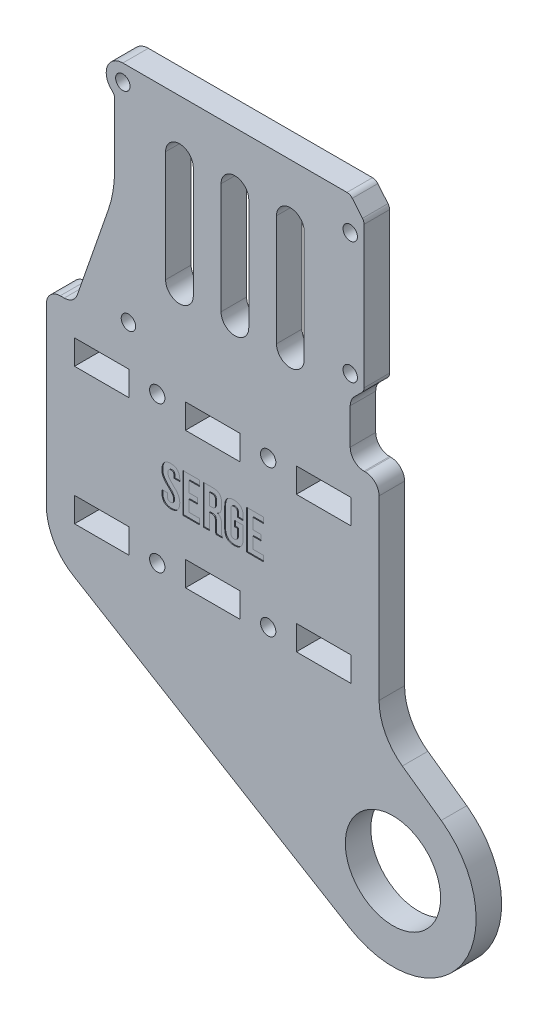
SolidWorks part; units mm, degrees
ref_plane "Front Plane" through (0, 0, 0) normal (0, 0, 1) x (1, 0, 0)
ref_plane "Top Plane" through (0, 0, 0) normal (0, 1, 0) x (1, 0, 0)
ref_plane "Right Plane" through (0, 0, 0) normal (1, 0, 0) x (0, 0, -1)
sketch "Sketch1" plane through (0, 0, 0) normal (0, 0, 1) x (1, 0, 0)
  line L0 (-38.1, 0) -> (38.1, 0) construction
  line L1 (31.65, -12.8) -> (19.15, -12.8)
  line L2 (38.1, -12.8) -> (38.1, 12.8)
  line L3 (31.65, 12.8) -> (19.15, 12.8)
  line L4 (-38.1, -12.8) -> (-38.1, 12.8)
  line L5 (38.1, -12.8) -> (-38.1, 12.8) construction
  line L6 (38.1, 12.8) -> (-38.1, -12.8) construction
  line L7 (6.25, 18.442) -> (-6.25, 18.442)
  line L8 (-19.15, -18.442) -> (-31.65, -12.8) construction
  line L9 (-19.15, -12.8) -> (-31.65, -18.442) construction
  line L10 (6.25, -12.8) -> (-6.25, -12.8)
  line L11 (-19.15, -12.8) -> (-31.65, -12.8)
  line L12 (31.65, -12.8) -> (31.65, -18.442)
  line L13 (19.15, -12.8) -> (19.15, -18.442)
  line L14 (12.6, 101.346) -> (12.6, 25.146) construction
  line L15 (-19.15, 12.8) -> (-19.15, 18.442)
  line L16 (-19.15, 18.442) -> (-31.65, 18.442)
  line L17 (-31.65, 12.8) -> (-31.65, 18.442)
  line L18 (-19.15, 12.8) -> (-31.65, 18.442) construction
  line L19 (-19.15, 18.442) -> (-31.65, 12.8) construction
  line L20 (-6.25, 12.8) -> (-6.25, 18.442)
  line L21 (6.25, 12.8) -> (6.25, 18.442)
  line L22 (31.65, 18.442) -> (19.15, 18.442)
  line L23 (19.15, 12.8) -> (19.15, 18.442)
  line L24 (31.65, 12.8) -> (31.65, 18.442)
  line L25 (-19.15, 12.8) -> (-31.65, 12.8)
  line L26 (6.25, 12.8) -> (-6.25, 12.8)
  line L27 (-38.1, 12.8) -> (-38.1, 25.146)
  line L28 (-38.1, 25.146) -> (-31.65, 25.146)
  line L29 (31.65, 25.146) -> (38.1, 25.146)
  line L30 (38.1, 25.146) -> (38.1, 12.8)
  line L31 (31.65, -18.442) -> (19.15, -18.442)
  line L32 (6.25, -12.8) -> (6.25, -18.442)
  line L33 (-6.25, -12.8) -> (-6.25, -18.442)
  line L34 (-31.65, -12.8) -> (-31.65, -18.442)
  line L35 (-19.15, -18.442) -> (-31.65, -18.442)
  line L36 (-19.15, -12.8) -> (-19.15, -18.442)
  line L37 (6.25, -18.442) -> (-6.25, -18.442)
  line L38 (31.65, -12.8) -> (19.15, -12.8)
  line L39 (-19.15, -12.8) -> (-31.65, -12.8)
  line L40 (6.25, -12.8) -> (-6.25, -12.8)
  line L41 (6.25, 12.8) -> (19.15, 12.8) construction
  line L42 (-38.1, -25.146) -> (31.4317, -67.1098)
  line L43 (38.1, -25.146) -> (52.3299, -35.2858)
  line L48 (-6.25, 12.8) -> (-19.15, 12.8) construction
  line L49 (31.65, 25.146) -> (31.65, 101.346)
  line L50 (31.65, 101.346) -> (-6.45, 101.346)
  line L51 (-6.45, 101.346) -> (-31.65, 25.146)
  line L52 (-6.45, 81.122) -> (-6.45, 25.146)
  line L53 (-6.45, 25.146) -> (-24.9618, 25.146)
  line L54 (-6.45, 81.122) -> (-24.9618, 25.146)
  line L55 (-38.1, -12.8) -> (-38.1, -25.146)
  line L56 (-0.4211, 99.3522) -> (-25.6211, 23.1522) construction
  line L58 (38.1, -12.8) -> (38.1, -25.146)
  arc A0 (31.4317, -67.1098) -> (52.3299, -35.2858) centre (41.275, -50.8) ccw
  circle A1 centre (12.7, 16.7687) radius 1.7526
  circle A2 centre (-12.7, 16.7687) radius 1.7526
  circle A3 centre (12.7, -16.7687) radius 1.7526
  circle A4 centre (-12.7, -16.7687) radius 1.7526
  circle A5 centre (12.6, 94.996) radius 2.413
  circle A6 centre (41.275, -50.8) radius 10.9125
  point P0 (0, 0)
  point P8 (-25.4, 15.621)
  point P37 (-25.4, -15.621)
  point P70 (-3.225, -28.575)
  dimension "D3" = 12.5
  dimension "D5" = 50.8
  dimension "D6" = 41.275
  dimension "D8" = 3.5052
  dimension "D13" = 3.5052
  dimension "D11" = 4.826
  dimension "D19" = 21.825
  dimension "D7" = 38.1
  dimension "D1" = 25.6
  dimension "D2" = 76.2
  dimension "D4" = 5.642
  dimension "D9" = 12.7
  dimension "D10" = 3
  dimension "D12" = 3.9688
  dimension "D14" = 3.9688
  dimension "D15" = 76.2
  dimension "D16" = 38.1
  dimension "D17" = 6.35
  dimension "D20" = 9.525
  dimension "D21" = 9.525
  dimension "D18" = 6.35
extrude "Boss-Extrude1" add sketch "Sketch1" along normal blind 5.842
fillet "Fillet1" radius 3.175 4 edges at (-38.1, 25.146, 2.921) (38.1, 25.146, 2.921) (-31.65, 25.146, 2.921) (31.65, 25.146, 2.921)
fillet "Fillet2" radius 3.175 3 edges at (-6.45, 25.146, 2.921) (-6.45, 81.122, 2.921) (-24.9618, 25.146, 2.921)
fillet "Fillet3" radius 3.175 2 edges at (31.65, 101.346, 2.921) (-6.45, 101.346, 2.921)
sketch "Sketch3" plane through (0, 0, 5.842) normal (0, 0, 1) x (1, 0, 0)
  line L0 (12.6, 94.996) -> (12.7, -16.7687) construction
  circle A0 centre (12.7136, -32.004) radius 2.413
  dimension "D1" = 4.826
  dimension "D2" = 127
extrude "Cut-Extrude2" [suppressed] cut sketch "Sketch3" against normal through all
sketch "Sketch5" plane through (0, 0, 5.842) normal (0, 0, 1) x (1, 0, 0)
  line L1 (-55.0734, 111.0269) -> (34.825, 111.0269)
  line L2 (-55.0734, 111.0269) -> (-55.0734, 25.146)
  line L3 (-55.0734, 25.146) -> (34.825, 25.146)
  line L4 (34.825, 111.0269) -> (34.825, 25.146)
extrude "Cut-Extrude3" cut sketch "Sketch5" against normal through all
sketch "Sketch6" plane through (0, 0, 5.842) normal (0, 0, 1) x (1, 0, 0)
  line L0 (-34.925, 25.146) -> (34.925, 25.146) construction
  line L1 (31.4879, 25.146) -> (-22.4871, 25.146)
  line L2 (31.4879, 78.486) -> (34.6629, 74.676)
  line L3 (31.4879, 78.486) -> (-20.5821, 78.486)
  line L4 (-22.4871, 25.146) -> (-25.0279, 25.146)
  line L5 (34.6629, 25.146) -> (-22.4871, 78.486) construction
  line L6 (34.6629, 78.486) -> (-22.4871, 25.146) construction
  line L7 (6.0879, 25.146) -> (6.0879, 48.411) construction
  line L8 (-31.75, 25.146) -> (-22.4871, 51.816)
  line L9 (-38.1, -25.146) -> (-38.1, 21.971) construction
  line L10 (34.6629, 74.676) -> (34.6629, 41.021)
  line L11 (-31.75, 25.146) -> (-25.0279, 25.146)
  line L12 (-22.4871, 51.816) -> (-22.4871, 71.3764)
  line L13 (31.4879, 70.866) -> (31.4879, 42.926) construction
  line L14 (31.4879, 37.846) -> (31.4879, 25.146)
  line L15 (31.4879, 37.846) -> (34.6629, 41.021)
  circle A0 centre (31.4879, 70.866) radius 1.651
  circle A1 centre (31.4879, 42.926) radius 1.651
  circle A2 centre (-20.5821, 74.676) radius 1.651
  circle A3 centre (-19.3121, 27.686) radius 1.651
  arc A4 (-20.5821, 78.486) -> (-22.4871, 71.3764) centre (-20.5821, 74.676) ccw
  point P0 (6.0879, 51.816)
  point P13 (-25.7515, 23.0626)
  point P14 (-16.4886, 49.7326)
  dimension "D5" = 3.302
  dimension "D6" = 3.302
  dimension "D9" = 12.7
  dimension "D10" = 3.302
  dimension "D12" = 3.302
  dimension "D1" = 53.34
  dimension "D2" = 57.15
  dimension "D3" = 6.35
  dimension "D7" = 49.53
  dimension "D8" = 27.94
  dimension "D11" = 52.07
  dimension "D13" = 50.8
  dimension "D14" = 15.24
  dimension "D4" = 7.62
extrude "Boss-Extrude3" add sketch "Sketch6" against normal up to surface (5.842 mm away) up to face at (52.1875, -50.8, 0)
fillet "Fillet6" radius 3.175 3 edges at (-31.75, 25.146, 2.921) (31.4879, 25.146, 2.921) (31.4879, 37.846, 2.921)
fillet "Fillet7" radius 1.5875 4 edges at (34.6629, 41.021, 2.921) (34.6629, 74.676, 2.921) (31.4879, 78.486, 2.921) (-22.4871, 71.3764, 2.921)
sketch "Sketch7" plane through (0, 0, 5.842) normal (0, 0, 1) x (1, 0, 0)
  line L0 (20.9561, 53.086) -> (-41.1495, 53.086) construction
  line L2 (5.0811, 78.486) -> (5.0811, 25.1147) construction
  line L3 (30.7443, 78.486) -> (-20.5821, 78.486) construction
  line L4 (5.0811, 65.786) -> (5.0811, 40.386) construction
  line L5 (8.2561, 65.786) -> (8.2561, 40.386)
  line L6 (1.9061, 65.786) -> (1.9061, 40.386)
  line L7 (17.7811, 65.786) -> (17.7811, 40.386) construction
  line L8 (20.9561, 65.786) -> (20.9561, 40.386)
  line L9 (14.6061, 65.786) -> (14.6061, 40.386)
  line L10 (-24.5007, 53.086) -> (20.9561, 53.086) construction
  line L11 (-7.6189, 65.786) -> (-7.6189, 40.386) construction
  line L12 (-10.7939, 65.786) -> (-10.7939, 40.386)
  line L13 (-4.4439, 65.786) -> (-4.4439, 40.386)
  arc A0 (8.2561, 65.786) -> (1.9061, 65.786) centre (5.0811, 65.786) ccw
  arc A1 (1.9061, 40.386) -> (8.2561, 40.386) centre (5.0811, 40.386) ccw
  arc A2 (20.9561, 65.786) -> (14.6061, 65.786) centre (17.7811, 65.786) ccw
  arc A3 (14.6061, 40.386) -> (20.9561, 40.386) centre (17.7811, 40.386) ccw
  arc A4 (-10.7939, 65.786) -> (-4.4439, 65.786) centre (-7.6189, 65.786) cw
  arc A5 (-4.4439, 40.386) -> (-10.7939, 40.386) centre (-7.6189, 40.386) cw
  point P10 (5.0811, 53.086)
  point P18 (17.7811, 53.086)
  point P26 (-7.6189, 53.086)
  dimension "D2" = 3.175
  dimension "D1" = 25.4
  dimension "D3" = 25.4
  dimension "D4" = 2
extrude "Cut-Extrude4" cut sketch "Sketch7" against normal through all
sketch "Sketch9" plane through (0, 0, 5.842) normal (0, 0, 1) x (1, 0, 0)
  line L0 (-38.1, -7.52) -> (38.1, -7.52) construction
  line L1 (-38.1, -25.146) -> (-38.1, 21.971) construction
  line L2 (38.1, 21.971) -> (38.1, -25.146) construction
  line L3 (-19.15, 12.8) -> (-31.65, 12.8) construction
  text T0 "SERGE" font "Roboto Condensed" height in points 42
  dimension "D1" = 20.32
extrude "Cut-Extrude5" [suppressed] cut sketch "Sketch9" against normal blind 0.3969
sketch "Sketch10" plane through (0, 0, 5.842) normal (0, 0, 1) x (1, 0, 0)
  line L0 (-38.1, -4.345) -> (38.1, -4.345) construction
  line L1 (-38.1, -25.146) -> (-38.1, 21.971) construction
  line L2 (38.1, 21.971) -> (38.1, -25.146) construction
  line L3 (-19.15, 12.8) -> (-31.65, 12.8) construction
  text T0 "SERGE" font "Bebas Neue" height in points 36
  dimension "D1" = 17.145
extrude "Cut-Extrude6" cut sketch "Sketch10" against normal blind 0.1984
sketch "Sketch11" [suppressed] plane through (0, 0, 5.842) normal (0, 0, 1) x (1, 0, 0)
  line L0 (12.6, 94.996) -> (12.7, 16.7687) construction
  line L1 (9.4669, 62.2324) -> (15.8169, 62.2324) construction
  line L2 (9.4669, 63.8199) -> (15.8169, 63.8199)
  line L3 (9.4669, 60.6449) -> (15.8169, 60.6449)
  line L4 (31.75, 55.8824) -> (-6.45, 55.8824) construction
  line L5 (-6.45, 61.4095) -> (-6.45, 28.321) construction
  line L6 (9.4506, 74.9324) -> (15.8006, 74.9324) construction
  line L7 (9.4506, 76.5199) -> (15.8006, 76.5199)
  line L8 (9.4506, 73.3449) -> (15.8006, 73.3449)
  line L9 (9.4344, 87.6324) -> (15.7844, 87.6324) construction
  line L10 (9.4344, 89.2199) -> (15.7844, 89.2199)
  line L11 (9.4344, 86.0449) -> (15.7844, 86.0449)
  line L12 (9.4344, 24.1324) -> (15.7844, 24.1324) construction
  line L13 (9.4344, 22.5449) -> (15.7844, 22.5449)
  line L14 (9.4344, 25.7199) -> (15.7844, 25.7199)
  line L15 (9.4506, 36.8324) -> (15.8006, 36.8324) construction
  line L16 (9.4506, 35.2449) -> (15.8006, 35.2449)
  line L17 (9.4506, 38.4199) -> (15.8006, 38.4199)
  line L18 (9.4669, 49.5324) -> (15.8169, 49.5324) construction
  line L19 (9.4669, 47.9449) -> (15.8169, 47.9449)
  line L20 (9.4669, 51.1199) -> (15.8169, 51.1199)
  arc A0 (9.4669, 63.8199) -> (9.4669, 60.6449) centre (9.4669, 62.2324) ccw
  arc A1 (15.8169, 60.6449) -> (15.8169, 63.8199) centre (15.8169, 62.2324) ccw
  arc A2 (9.4506, 76.5199) -> (9.4506, 73.3449) centre (9.4506, 74.9324) ccw
  arc A3 (15.8006, 73.3449) -> (15.8006, 76.5199) centre (15.8006, 74.9324) ccw
  arc A4 (9.4344, 89.2199) -> (9.4344, 86.0449) centre (9.4344, 87.6324) ccw
  arc A5 (15.7844, 86.0449) -> (15.7844, 89.2199) centre (15.7844, 87.6324) ccw
  arc A6 (9.4344, 22.5449) -> (9.4344, 25.7199) centre (9.4344, 24.1324) cw
  arc A7 (15.7844, 25.7199) -> (15.7844, 22.5449) centre (15.7844, 24.1324) cw
  arc A8 (9.4506, 35.2449) -> (9.4506, 38.4199) centre (9.4506, 36.8324) cw
  arc A9 (15.8006, 38.4199) -> (15.8006, 35.2449) centre (15.8006, 36.8324) cw
  arc A10 (9.4669, 47.9449) -> (9.4669, 51.1199) centre (9.4669, 49.5324) cw
  arc A11 (15.8169, 51.1199) -> (15.8169, 47.9449) centre (15.8169, 49.5324) cw
  point P6 (12.6419, 62.2324)
  point P16 (12.65, 55.8824)
  point P19 (12.6256, 74.9324)
  point P26 (12.6094, 87.6324)
  point P32 (12.6094, 24.1324)
  point P39 (12.6256, 36.8324)
  point P46 (12.6419, 49.5324)
  dimension "D1" = 1.5875
  dimension "D2" = 6.35
  dimension "D3" = 6.35
  dimension "D4" = 3
extrude "Cut-Extrude7" [suppressed] cut sketch "Sketch11" against normal through all
fillet "Fillet8" radius 25.4 1 edges at (-22.4871, 51.816, 2.921)
fillet "Fillet10" radius 12.7 1 edges at (-38.1, -25.146, 2.921)
fillet "Fillet11" radius 12.7 1 edges at (38.1, -25.146, 2.921)
